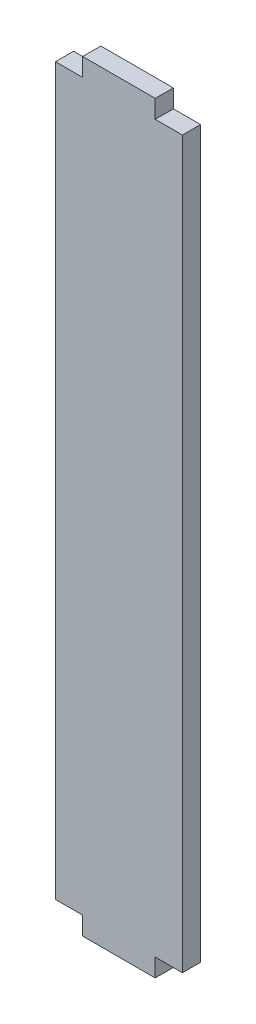
SolidWorks part; units mm, degrees
ref_plane "Front Plane" through (0, 0, 0) normal (0, 0, 1) x (1, 0, 0)
ref_plane "Top Plane" through (0, 0, 0) normal (0, 1, 0) x (1, 0, 0)
ref_plane "Right Plane" through (0, 0, 0) normal (1, 0, 0) x (0, 0, -1)
sketch "Sketch1" plane through (0, 0, 0) normal (0, 0, 1) x (1, 0, 0)
  line L0 (-35, -100) -> (-67.4424, -100) construction
  line L1 (0, 0) -> (-35, 0)
  line L2 (0, 0) -> (0, -200)
  line L3 (0, -200) -> (-35, -200)
  line L4 (-35, 0) -> (-35, -200)
  line L5 (-27.5, 0) -> (-7.5, 0)
  line L6 (-27.5, 0) -> (-27.5, 5)
  line L7 (-27.5, 5) -> (-7.5, 5)
  line L8 (-7.5, 0) -> (-7.5, 5)
  line L9 (-27.5, -205) -> (-7.5, -205)
  line L10 (-7.5, -200) -> (-7.5, -205)
  line L11 (-27.5, -200) -> (-7.5, -200)
  line L12 (-27.5, -200) -> (-27.5, -205)
  dimension "D1" = 200
  dimension "D2" = 35
  dimension "D3" = 20
  dimension "D4" = 7.5
  dimension "D5" = 5
extrude "Boss-Extrude1" add sketch "Sketch1" along normal blind 5 contours L1 L4 L3 L2 | L1 L8 L7 L6 | L3 L12 L9 L10
